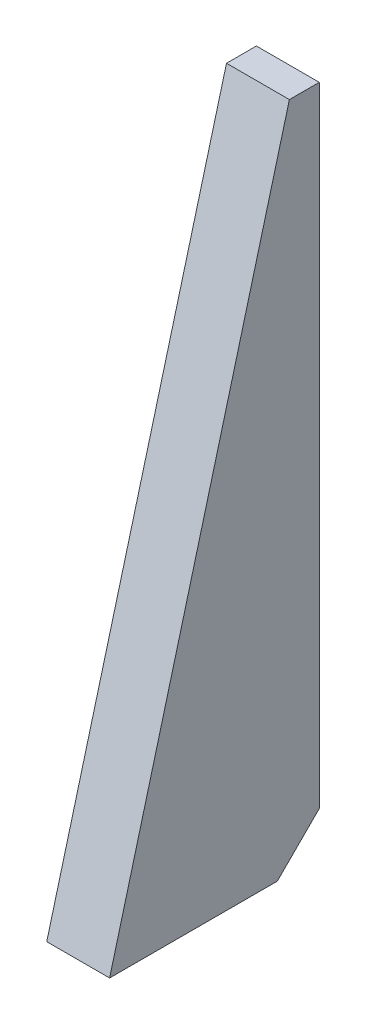
SolidWorks part; units mm, degrees
ref_plane "Front Plane" through (0, 0, 0) normal (0, 0, 1) x (1, 0, 0)
ref_plane "Top Plane" through (0, 0, 0) normal (0, 1, 0) x (1, 0, 0)
ref_plane "Right Plane" through (0, 0, 0) normal (1, 0, 0) x (0, 0, -1)
sketch "Sketch1" plane through (0, 0, 0) normal (1, 0, 0) x (0, 0, -1)
  line L0 (-10, 0) -> (-50, 0)
  line L1 (0, 10) -> (0, 160)
  line L2 (-50, 0) -> (-7.1281, 160)
  line L3 (0, 160) -> (-7.1281, 160)
  line L4 (0, 10) -> (-10, 0)
  point P0 (0, 0)
  point P3 (0, 0)
  dimension "D1" = 50
  dimension "D2" = 160
  dimension "D3" = 75
  dimension "D4" = 10
  dimension "D5" = 45
extrude "Boss-Extrude1" add sketch "Sketch1" along normal blind 15
